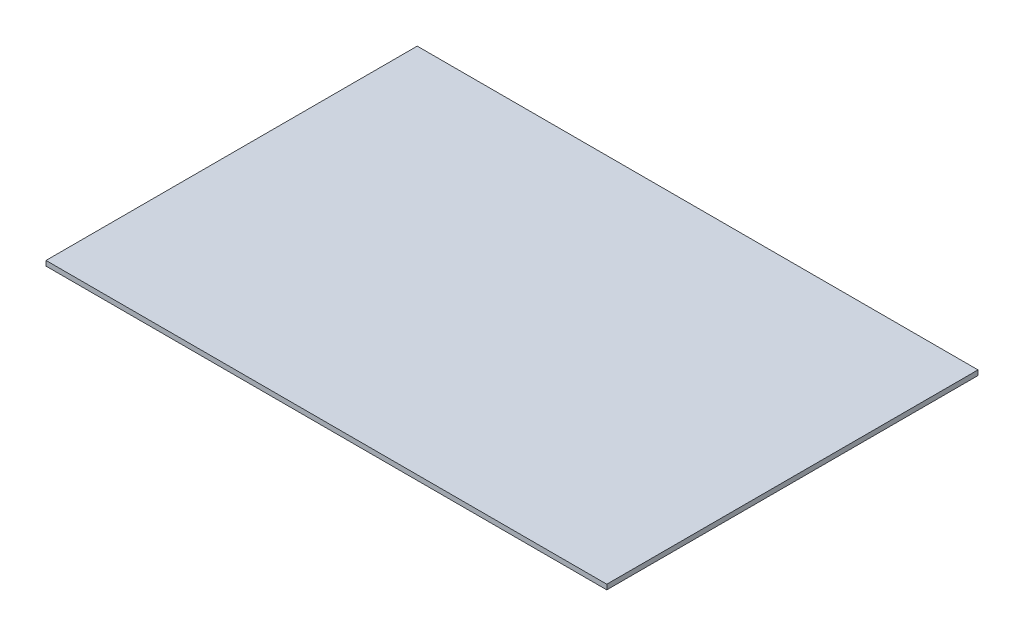
SolidWorks part; units mm, degrees
material "Acrylic (Medium-high impact)"
ref_plane "Front Plane" through (0, 0, 0) normal (0, 0, 1) x (1, 0, 0)
ref_plane "Top Plane" through (0, 0, 0) normal (0, 1, 0) x (1, 0, 0)
ref_plane "Right Plane" through (0, 0, 0) normal (1, 0, 0) x (0, 0, -1)
sketch "Sketch2" plane through (0, 0, 0) normal (0, 1, 0) x (1, 0, 0)
  line L1 (0, 0) -> (901.7, 0)
  line L2 (0, 0) -> (0, 596.9)
  line L3 (0, 596.9) -> (901.7, 596.9)
  line L4 (901.7, 0) -> (901.7, 596.9)
  dimension "D1" = 901.7
  dimension "D2" = 596.9
extrude "Boss-Extrude2" add sketch "Sketch2" along normal blind 7.9375
